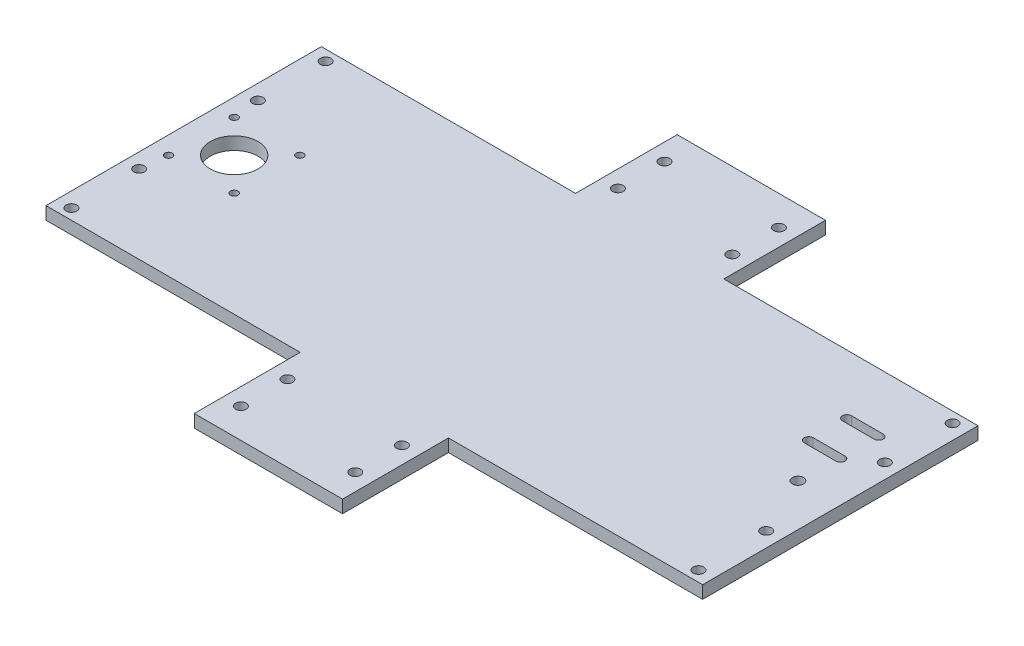
SolidWorks part; units mm, degrees
ref_plane "Alzado" through (0, 0, 0) normal (0, 0, 1) x (1, 0, 0)
ref_plane "Planta" through (0, 0, 0) normal (0, 1, 0) x (1, 0, 0)
ref_plane "Vista lateral" through (0, 0, 0) normal (1, 0, 0) x (0, 0, -1)
sketch "Croquis1" plane through (0, 0, 0) normal (0, 1, 0) x (1, 0, 0)
  line L0 (-15, 65) -> (-15, -66.8009) construction
  line L1 (-155, -65) -> (-43.3979, -65)
  line L2 (-155, -65) -> (-155, 65)
  line L3 (-155, 65) -> (-43.3979, 65)
  line L4 (155, -65) -> (155, 65)
  line L5 (-155, -65) -> (155, 65) construction
  line L6 (-155, 65) -> (155, -65) construction
  line L7 (-95, 65) -> (-95, -66.8009) construction
  line L8 (65, 65) -> (65, -66.8009) construction
  line L9 (-155, 0) -> (155, 0) construction
  line L10 (-141, -44) -> (-155, -44) construction
  line L11 (-146.655, -15.495) -> (-115.665, -15.495) construction
  line L12 (-146.655, -15.495) -> (-146.655, 15.495) construction
  line L13 (-146.655, 15.495) -> (-115.665, 15.495) construction
  line L14 (-115.665, -15.495) -> (-115.665, 15.495) construction
  line L15 (-146.655, -15.495) -> (-115.665, 15.495) construction
  line L16 (-146.655, 15.495) -> (-115.665, -15.495) construction
  line L17 (-155, -65) -> (-141, -65) construction
  line L18 (-155, -65) -> (-155, -23) construction
  line L19 (-155, -23) -> (-141, -23) construction
  line L20 (-141, -65) -> (-141, -23) construction
  line L21 (-148, -44) -> (-148, -23) construction
  line L22 (-148, -44) -> (-148, -65) construction
  line L23 (51, 65) -> (155, 65)
  line L25 (-35, 71) -> (-35, 107)
  line L26 (-29, 113) -> (29, 113)
  line L27 (35, 71) -> (35, 107)
  line L29 (-35, -71) -> (-35, -109)
  line L30 (-29, -115) -> (29, -115)
  line L31 (35, -71) -> (35, -109)
  line L32 (51, -65) -> (155, -65)
  line L33 (0, 113) -> (0, 99) construction
  line L34 (0, 99) -> (-35, 99) construction
  line L35 (0, -115) -> (0, -101) construction
  line L36 (0, -101) -> (35, -101) construction
  line L37 (-43.3979, -65) -> (-35, -65)
  line L38 (-35, -71) -> (-35, -65)
  line L39 (51, -65) -> (35, -65)
  line L40 (35, -65) -> (35, -71)
  line L41 (148, -60) -> (148, -28) construction
  line L42 (29, -115) -> (35, -115)
  line L45 (35, -115) -> (35, -109)
  line L46 (-29, -115) -> (-35, -115)
  line L49 (-35, -115) -> (-35, -109)
  line L50 (-43.3979, 65) -> (-35, 65)
  line L53 (-35, 65) -> (-35, 71)
  line L54 (51, 65) -> (35, 65)
  line L57 (35, 65) -> (35, 71)
  line L59 (35, 107) -> (35, 113)
  line L60 (35, 113) -> (29, 113)
  line L62 (-29, 113) -> (-35, 113)
  line L65 (-35, 113) -> (-35, 107)
  circle A0 centre (-146.655, 15.495) radius 1.75
  circle A1 centre (-115.665, 15.495) radius 1.75
  circle A2 centre (-115.665, -15.495) radius 1.75
  circle A3 centre (-146.655, -15.495) radius 1.75
  circle A4 centre (-131.16, 0) radius 11.25
  circle A5 centre (135, 0) radius 2.65
  circle A6 centre (-148, -60) radius 2.5
  circle A7 centre (-148, -28) radius 2.5
  circle A8 centre (148, -60) radius 2.5
  circle A9 centre (148, -28) radius 2.5
  circle A10 centre (148, 60) radius 2.5
  circle A11 centre (148, 28) radius 2.5
  circle A12 centre (-148, 60) radius 2.5
  circle A13 centre (-148, 28) radius 2.5
  circle A22 centre (-27, 99) radius 2.5
  circle A23 centre (-27, 77) radius 2.5
  circle A24 centre (27, 77) radius 2.5
  circle A25 centre (27, 99) radius 2.5
  circle A26 centre (27, -101) radius 2.5
  circle A27 centre (27, -79) radius 2.5
  circle A28 centre (-27, -101) radius 2.5
  circle A29 centre (-27, -79) radius 2.5
  point P0 (0, 0)
  point P14 (-131.16, 0)
  point P63 (35, 113)
  point P66 (35, -115)
  point P69 (-35, -115)
  point P74 (35, -65)
  point P77 (35, 65)
  dimension "D8" = 3.5
  dimension "D9" = 3.5
  dimension "D10" = 3.5
  dimension "D11" = 3.5
  dimension "D12" = 22.5
  dimension "D13" = 5.3
  dimension "D17" = 5
  dimension "D18" = 5
  dimension "D28" = 7
  dimension "D30" = 5
  dimension "D32" = 5
  dimension "D35" = 5
  dimension "D37" = 5
  dimension "D38" = 22
  dimension "D1" = 310
  dimension "D2" = 130
  dimension "D5" = 60
  dimension "D6" = 30.99
  dimension "D7" = 30.99
  dimension "D14" = 20
  dimension "D15" = 14
  dimension "D16" = 42
  dimension "D19" = 16
  dimension "D20" = 16
  dimension "D22" = 48
  dimension "D23" = 70
  dimension "D24" = 35
  dimension "D25" = 70
  dimension "D26" = 50
  dimension "D27" = 35
  dimension "D29" = 14
  dimension "D31" = 8
  dimension "D33" = 22
  dimension "D34" = 14
  dimension "D36" = 8
  dimension "D39" = 23.84
  dimension "D3" = 80
  dimension "D4" = 80
  dimension "D21" = 2
extrude "Saliente-Extruir1" add sketch "Croquis1" along normal blind 6
sketch "Croquis3" plane through (0, 6, 0) normal (0, 1, 0) x (1, 0, 0)
  line L0 (136, 37.1) -> (121, 37.1) construction
  line L1 (136, 35) -> (121, 35)
  line L2 (136, 39.2) -> (121, 39.2)
  line L3 (155, 65) -> (35, 65) construction
  line L4 (155, -65) -> (155, 65) construction
  line L5 (141.6097, 28.1) -> (98.9184, 28.1) construction
  line L6 (136, 19.1) -> (121, 19.1) construction
  line L7 (136, 21.2) -> (121, 21.2)
  line L8 (136, 17) -> (121, 17)
  arc A0 (136, 35) -> (136, 39.2) centre (136, 37.1) ccw
  arc A1 (121, 39.2) -> (121, 35) centre (121, 37.1) ccw
  arc A2 (136, 21.2) -> (136, 17) centre (136, 19.1) cw
  arc A3 (121, 17) -> (121, 21.2) centre (121, 19.1) cw
  point P2 (128.5, 37.1)
  point P15 (128.5, 19.1)
  dimension "D2" = 2.1
  dimension "D1" = 15
  dimension "D3" = 30
  dimension "D4" = 34
  dimension "D5" = 13.8
extrude "Cortar-Extruir1" cut sketch "Croquis3" against normal through all
